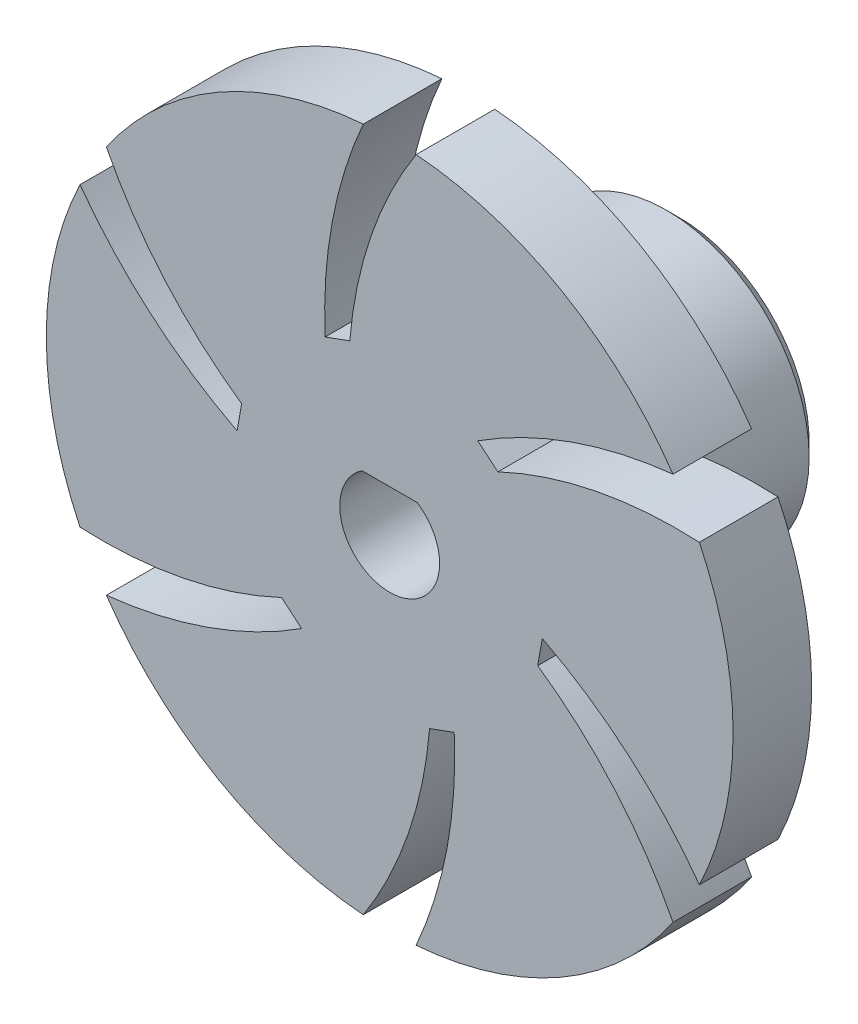
SolidWorks part; units mm, degrees
material "ABS"
ref_plane "Front Plane" through (0, 0, 0) normal (0, 0, 1) x (1, 0, 0)
ref_plane "Top Plane" through (0, 0, 0) normal (0, 1, 0) x (1, 0, 0)
ref_plane "Right Plane" through (0, 0, 0) normal (1, 0, 0) x (0, 0, -1)
sketch "Sketch1" plane through (0, 0, 0) normal (0, 0, 1) x (1, 0, 0)
  circle A0 centre (0, 0) radius 20.6375
  dimension "D1" = 41.275
extrude "Boss-Extrude1" add sketch "Sketch1" along normal mid plane 4.7244
sketch "Sketch2" plane through (0, 0, 2.3622) normal (0, 0, 1) x (1, 0, 0)
  line L0 (-2.3978, 8.89) -> (-3.8776, 8.3514)
  line L2 (-3.1377, 8.6207) -> (0, 0) construction
  line L3 (0, 20.6375) -> (0, 0) construction
  circle A0 centre (0, 0) radius 20.6375 construction
  arc A1 (1.5875, 20.5764) -> (-1.5875, 20.5764) centre (0, 0) ccw
  arc A2 (-2.3978, 8.89) -> (1.5875, 20.5764) centre (22.9145, 6.7807) cw
  arc A3 (-3.8776, 8.3514) -> (-1.5875, 20.5764) centre (23.0668, 9.6309) cw
  point P13 (0, 20.6375)
  dimension "D2" = 3.175
  dimension "D4" = 25.4
  dimension "D5" = 26.9748
  dimension "D1" = 20
  dimension "D3" = 1.5748
  dimension "D6" = 8.89
extrude "Cut-Extrude1" cut sketch "Sketch2" against normal through all
sketch "Sketch4" plane through (0, 0, -2.3622) normal (0, 0, -1) x (-1, 0, 0)
  circle A0 centre (0, 0) radius 8.5725
  dimension "D1" = 17.145
extrude "Boss-Extrude2" add sketch "Sketch4" along normal blind 12.7
pattern_circular "CirPattern1" count 6 over 360 about axis through (0, 0, 0) along (0, 0, 1) of "Cut-Extrude1"
sketch "Sketch3" plane through (0, 0, 2.3622) normal (0, 0, 1) x (1, 0, 0)
  line L0 (-1.6583, 2.5) -> (1.6583, 2.5)
  arc A0 (-1.6583, 2.5) -> (1.6583, 2.5) centre (0, 0) ccw
  point P1 (0, -3)
  dimension "D1" = 6
  dimension "D2" = 5.5
extrude "Cut-Extrude2" cut sketch "Sketch3" against normal through all
chamfer "Chamfer1" distance 0.7874 angle 45 1 edges at (-8.5725, 0, -15.0622)
